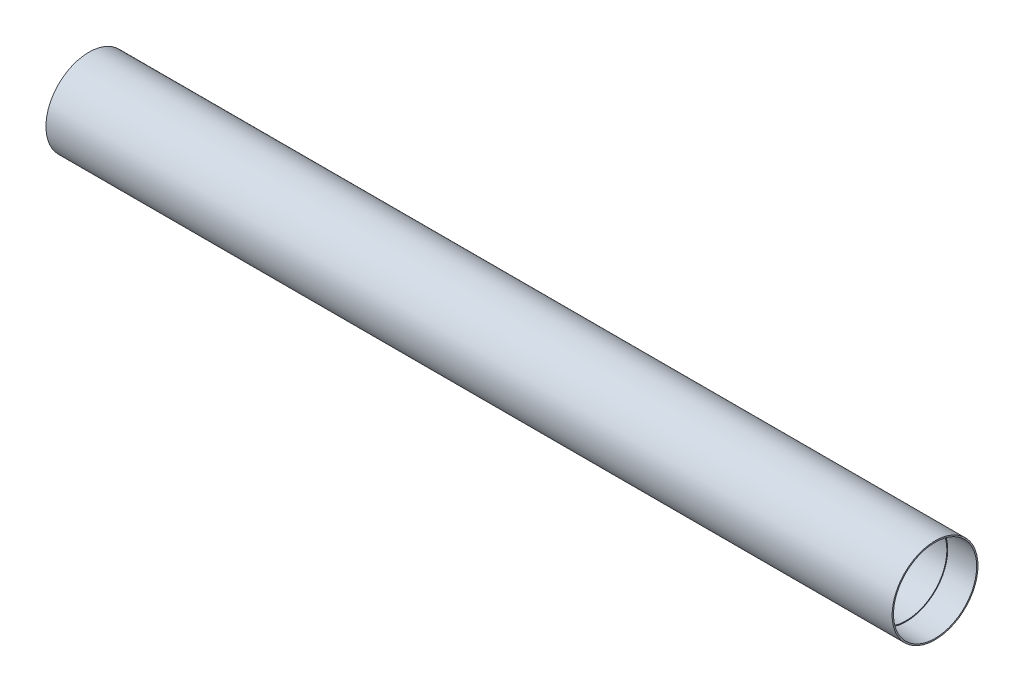
SolidWorks part; units mm, degrees
ref_plane "Front Plane" through (0, 0, 0) normal (0, 0, 1) x (1, 0, 0)
ref_plane "Top Plane" through (0, 0, 0) normal (0, 1, 0) x (1, 0, 0)
ref_plane "Right Plane" through (0, 0, 0) normal (1, 0, 0) x (0, 0, -1)
sketch "Sketch1" plane through (0, 0, 0) normal (1, 0, 0) x (0, 0, -1)
  circle A0 centre (0, 0) radius 37.6555
  dimension "D1" = 75.311
extrude "Boss-Extrude1" add sketch "Sketch1" along normal blind 742.3404
sketch "Sketch4" plane through (742.3404, 0, 0) normal (1, 0, 0) x (0, 0, -1)
  circle A0 centre (0, 0) radius 36.5
  dimension "D1" = 73
extrude "Cut-Extrude2" cut sketch "Sketch4" against normal blind 25.4
sketch "Sketch5" plane through (0, 0, 0) normal (-1, 0, 0) x (0, 0, 1)
  circle A0 centre (0, 0) radius 36.5
  dimension "D1" = 73
extrude "Cut-Extrude3" cut sketch "Sketch5" against normal blind 25.4
sketch "Sketch6" plane through (716.9404, 0, 0) normal (1, 0, 0) x (0, 0, -1)
  circle A0 centre (0, 0) radius 35.75
  dimension "D1" = 71.5
extrude "Cut-Extrude4" cut sketch "Sketch6" against normal through all
